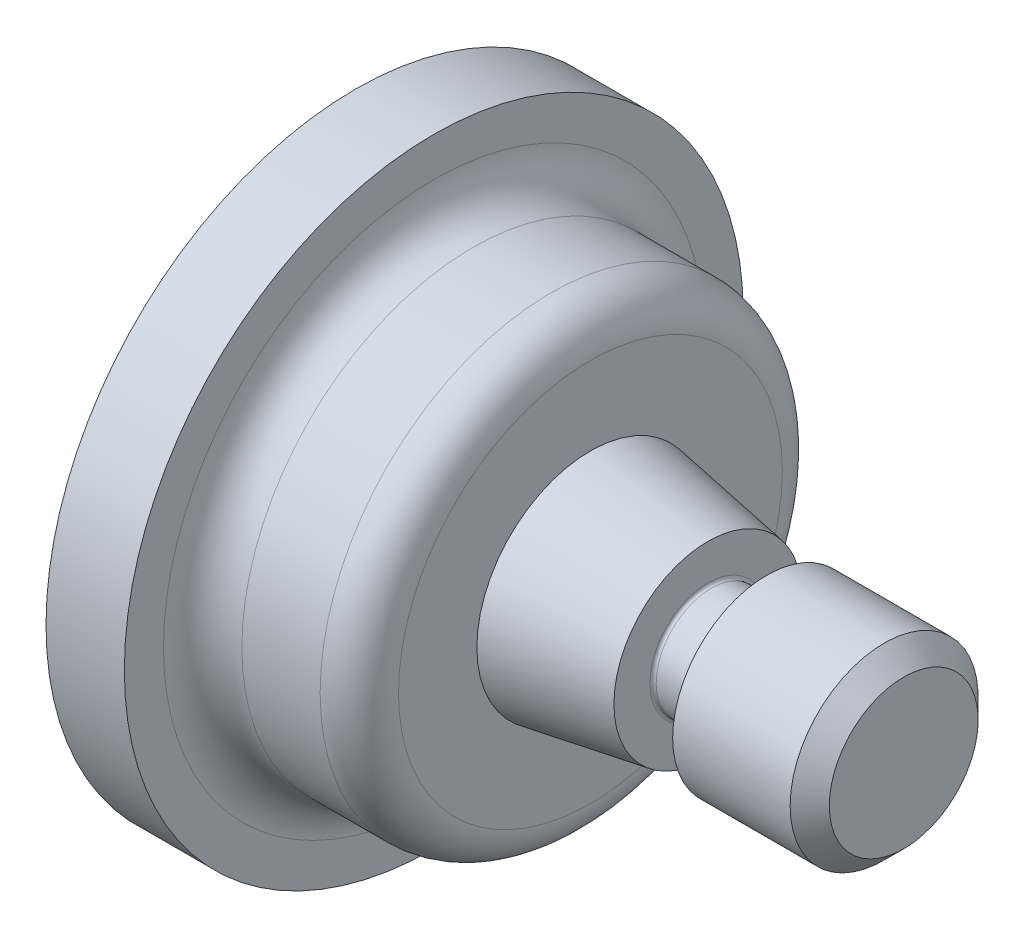
SolidWorks part; units mm, degrees
ref_plane "Plane1" through (0, 0, 0) normal (0, 0, 1) x (1, 0, 0)
ref_plane "Plane2" through (0, 0, 0) normal (0, 1, 0) x (1, 0, 0)
ref_plane "Plane3" through (0, 0, 0) normal (1, 0, 0) x (0, 0, -1)
sketch "Sketch1" plane through (0, 0, 0) normal (0, 0, 1) x (1, 0, 0)
  line L0 (-88.9, 50.165) -> (-76.1987, 50.165)
  line L1 (-57.15, 37.4662) -> (-69.85, 37.4662)
  line L2 (-31.242, 8.89) -> (-22.733, 8.89)
  line L3 (-50.7988, 31.115) -> (-50.7988, 18.4148)
  line L4 (0, 0) -> (20.955, 0) construction
  line L5 (-50.7988, 18.4148) -> (-31.75, 15.24)
  line L6 (-22.225, 15.24) -> (-3.175, 15.24)
  line L7 (-3.175, 15.24) -> (0, 12.065)
  line L8 (0, 0) -> (0, 12.065)
  line L9 (-22.225, 15.24) -> (-22.225, 9.398)
  line L10 (-31.75, 15.24) -> (-31.75, 9.398)
  line L11 (-76.1987, 50.165) -> (-76.1987, 43.815)
  line L12 (-88.9, 50.165) -> (-88.9, 0)
  line L13 (46.4569, 0) -> (54.8389, 0) construction
  line L14 (0, 0) -> (-88.9, 0)
  arc A0 (-57.15, 37.4662) -> (-50.7988, 31.115) centre (-57.15, 31.115) cw
  arc A1 (-76.1987, 43.815) -> (-69.85, 37.4662) centre (-69.85, 43.815) ccw
  arc A2 (-22.733, 8.89) -> (-22.225, 9.398) centre (-22.733, 9.398) ccw
  arc A3 (-31.242, 8.89) -> (-31.75, 9.398) centre (-31.242, 9.398) cw
revolve "Base-Revolve" add sketch "Sketch1" angle 360 about L4
sketch "Stock Profile" plane through (0, 0, 0) normal (0, 0, 1) x (1, 0, 0)
  line L0 (-96.52, 50.165) -> (-96.52, 0)
  line L2 (4.92, 25.875) -> (-30.502, 25.875)
  line L4 (-31.3371, 25.9441) -> (-36.5552, 26.8138)
  line L6 (-40.8, 31.8247) -> (-40.8, 45.085)
  line L8 (10, 0) -> (10, 20.795)
  line L9 (-96.52, 0) -> (10, 0)
  line L10 (-45.88, 50.165) -> (-96.52, 50.165)
  arc A0 (4.92, 25.875) -> (10, 20.795) centre (4.92, 20.795) cw
  arc A1 (-30.502, 25.875) -> (-31.3371, 25.9441) centre (-30.502, 30.955) cw
  arc A2 (-45.88, 50.165) -> (-40.8, 45.085) centre (-45.88, 45.085) cw
  arc A3 (-40.8, 31.8247) -> (-36.5552, 26.8138) centre (-35.72, 31.8247) ccw
  dimension "D5" = 5.08
  dimension "D6" = 5.08
